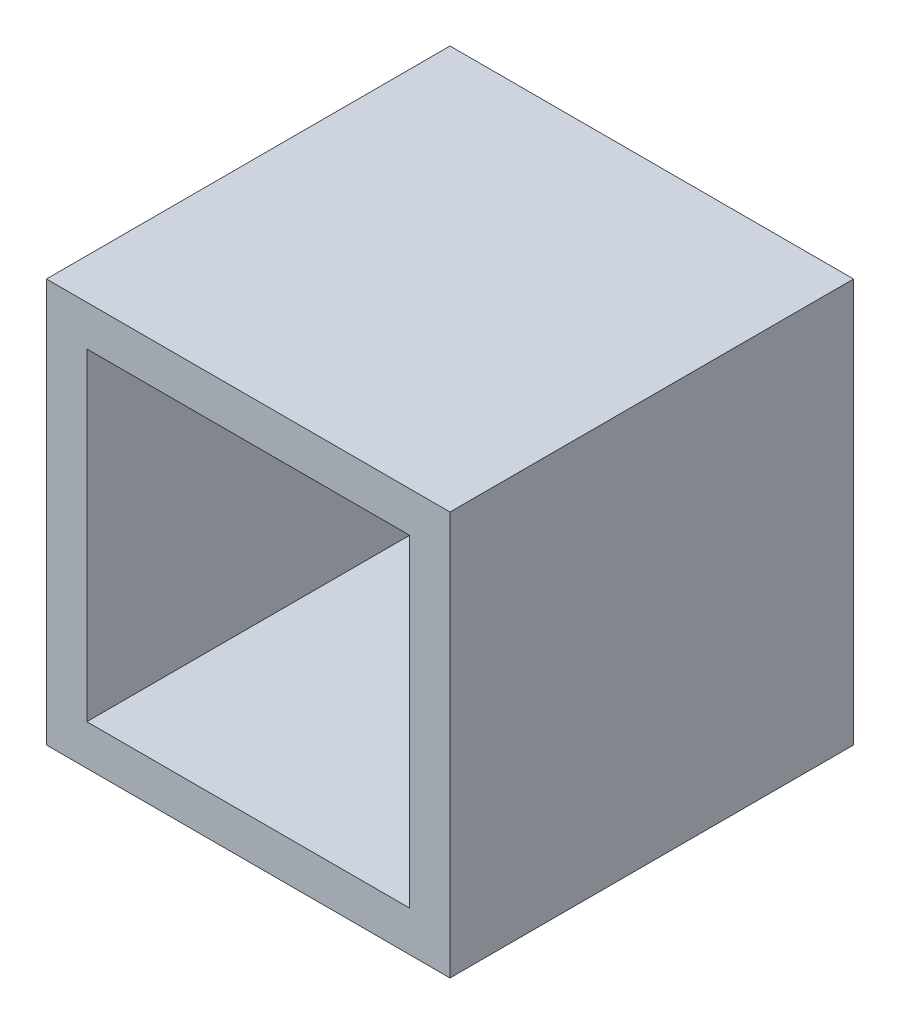
SolidWorks part; units mm, degrees
ref_plane "前视基准面" through (0, 0, 0) normal (0, 0, 1) x (1, 0, 0)
ref_plane "上视基准面" through (0, 0, 0) normal (0, 1, 0) x (1, 0, 0)
ref_plane "右视基准面" through (0, 0, 0) normal (1, 0, 0) x (0, 0, -1)
sketch "草图1" plane through (0, 0, 0) normal (0, 0, 1) x (1, 0, 0)
  line L1 (-5, -5) -> (5, -5)
  line L2 (-5, -5) -> (-5, 5)
  line L3 (-5, 5) -> (5, 5)
  line L4 (5, -5) -> (5, 5)
  line L5 (-5, -5) -> (5, 5) construction
  line L6 (-5, 5) -> (5, -5) construction
  line L7 (-4, -4) -> (4, -4)
  line L8 (-4, -4) -> (-4, 4)
  line L9 (-4, 4) -> (4, 4)
  line L10 (4, -4) -> (4, 4)
  line L11 (-4, -4) -> (4, 4) construction
  line L12 (-4, 4) -> (4, -4) construction
  point P0 (0, 0)
  point P10 (0, 0)
  dimension "D1" = 10
  dimension "D2" = 10
  dimension "D3" = 8
extrude "凸台-拉伸1" add sketch "草图1" along normal blind 10
